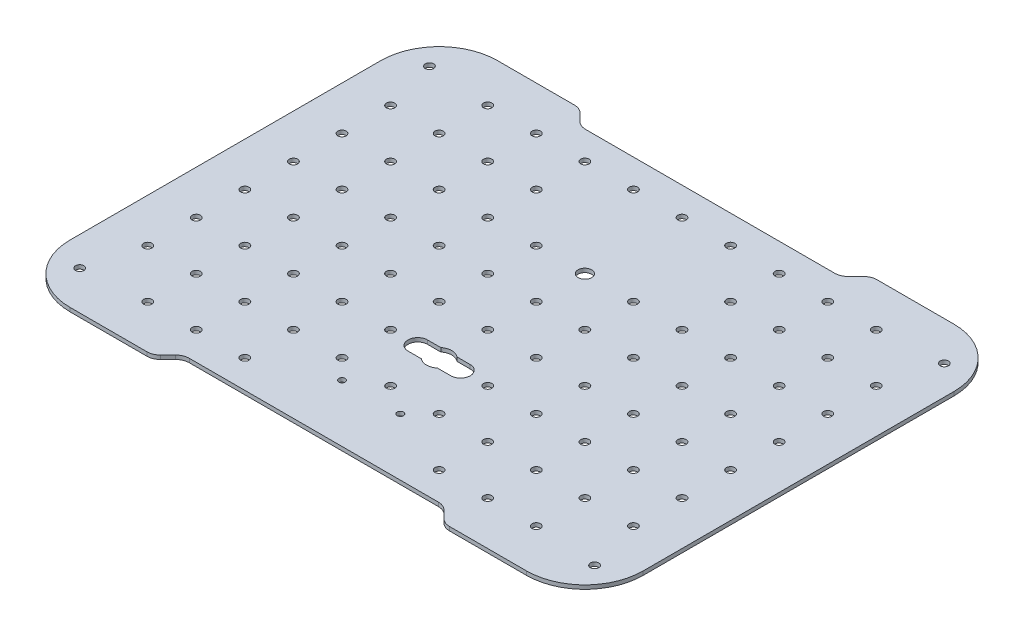
SolidWorks part; units mm, degrees
ref_plane "Front Plane" through (0, 0, 0) normal (0, 0, 1) x (1, 0, 0)
ref_plane "Top Plane" through (0, 0, 0) normal (0, 1, 0) x (1, 0, 0)
ref_plane "Right Plane" through (0, 0, 0) normal (1, 0, 0) x (0, 0, -1)
sketch "Sketch1" plane through (0, 0, 0) normal (0, 1, 0) x (1, 0, 0)
  line L0 (0, 110) -> (0, 0) construction
  line L5 (117.5, -110) -> (-117.5, -110)
  line L6 (147.5, -80) -> (147.5, 80)
  line L7 (117.5, 110) -> (-117.5, 110)
  line L8 (-147.5, -80) -> (-147.5, 80)
  line L9 (0, 0) -> (147.5, 0) construction
  arc A4 (117.5, 110) -> (147.5, 80) centre (117.5, 80) cw
  arc A5 (147.5, -80) -> (117.5, -110) centre (117.5, -80) cw
  arc A6 (-117.5, -110) -> (-147.5, -80) centre (-117.5, -80) cw
  arc A7 (-147.5, 80) -> (-117.5, 110) centre (-117.5, 80) cw
  point P0 (0, 0)
  dimension "D3" = 220
  dimension "D1" = 30
  dimension "D2" = 295
ref_plane "Plane1" through (0, -40, 0) normal (0, 1, 0) x (1, 0, 0)
sketch "Sketch8" plane through (0, 0, 0) normal (0, 1, 0) x (1, 0, 0)
  line L1 (-132.5, -90) -> (132.5, -90) construction
  line L2 (-132.5, -90) -> (-132.5, 90) construction
  line L3 (-132.5, 90) -> (132.5, 90) construction
  line L4 (132.5, -90) -> (132.5, 90) construction
  line L5 (-132.5, -90) -> (132.5, 90) construction
  line L6 (-132.5, 90) -> (132.5, -90) construction
  circle A0 centre (-132.5, 90) radius 2.15
  circle A1 centre (132.5, 90) radius 2.15
  circle A2 centre (-132.5, -90) radius 2.15
  circle A3 centre (132.5, -90) radius 2.15
  point P0 (0, 0)
  dimension "D1" = 4.3
  dimension "D2" = 265
  dimension "D3" = 180
extrude "Boss-Extrude1" add sketch "Sketch1" against normal blind 2
extrude "Cut-Extrude11" cut sketch "Sketch8" against normal through all
sketch "Sketch9" plane through (0, 0, 0) normal (0, 1, 0) x (1, 0, 0)
  line L0 (-75, -110) -> (-67, -102)
  line L1 (-117.5, -110) -> (117.5, -110) construction
  line L2 (-67, -102) -> (67, -102)
  line L3 (67, -102) -> (75, -110)
  line L4 (75, -110) -> (-75, -110)
  line L5 (0, -110) -> (0, -102) construction
  line L6 (0, -102) -> (0, 0) construction
  dimension "D1" = 150
  dimension "D2" = 135
  dimension "D3" = 8
extrude "Cut-Extrude12" cut sketch "Sketch9" against normal through all
mirror "Mirror2" about plane through (0, 0, 0) normal (0, 0, 1) of "Cut-Extrude12"
fillet "Fillet1" radius 7 8 edges at (-67, -1, 102) (67, -1, 102) (75, -1, 110) (-75, -1, 110) (-75, -1, -110) (75, -1, -110) (-67, -1, -102) (67, -1, -102)
sketch "Sketch11" plane through (0, 0, 0) normal (0, 1, 0) x (1, 0, 0)
  line L0 (0, 0) -> (0, -37.5) construction
  circle A0 centre (0, -37.5) radius 6.5
  dimension "D2" = 13
  dimension "D1" = 37.5
extrude "Cut-Extrude14" cut sketch "Sketch11" against normal through all
sketch "Sketch10" plane through (0, 0, 0) normal (0, 1, 0) x (1, 0, 0)
  line L0 (0, 0) -> (0, -37.5) construction
  line L1 (125, -87.5) -> (-125, -87.5) construction
  line L2 (125, -87.5) -> (125, 87.5) construction
  line L3 (125, 87.5) -> (-125, 87.5) construction
  line L4 (-125, -87.5) -> (-125, 87.5) construction
  line L5 (125, -87.5) -> (-125, 87.5) construction
  line L6 (125, 87.5) -> (-125, -87.5) construction
  circle A1 centre (-125, 87.5) radius 2.15
  point P0 (0, 0)
  dimension "D3" = 4.3
  dimension "D1" = 250
  dimension "D4" = 125
  dimension "D5" = 175
extrude "Cut-Extrude13" cut sketch "Sketch10" against normal through all
pattern_linear "LPattern1" count 8 spacing 25 along (0, 0, 1) count 11 spacing 25 along (1, 0, 0) skipping (1, 4), (1, 5), (1, 6), (5, 5), (7, 4), (7, 5), (7, 6) of "Cut-Extrude13"
sketch "Sketch18" plane through (0, 0, 0) normal (0, 1, 0) x (1, 0, 0)
  line L0 (-15, -72.5) -> (15, -72.5) construction
  line L1 (0, -72.5) -> (0, -102) construction
  line L2 (64.1005, -102) -> (-64.1005, -102) construction
  circle A0 centre (15, -72.5) radius 1.65
  circle A1 centre (-15, -72.5) radius 1.65
  dimension "D3" = 3.3
  dimension "D1" = 29.5
  dimension "D2" = 30
extrude "Cut-Extrude21" cut sketch "Sketch18" against normal through all
sketch "Sketch19" plane through (0, 0, 0) normal (0, 1, 0) x (1, 0, 0)
  line L0 (-11, -37.5) -> (11, -37.5) construction
  line L1 (-11, -32.5) -> (11, -32.5)
  line L2 (-11, -42.5) -> (11, -42.5)
  arc A0 (-11, -32.5) -> (-11, -42.5) centre (-11, -37.5) ccw
  arc A1 (11, -42.5) -> (11, -32.5) centre (11, -37.5) ccw
  point P2 (0, -37.5)
  dimension "D1" = 10
  dimension "D2" = 22
extrude "Cut-Extrude22" cut sketch "Sketch19" against normal blind 10
sketch "Sketch20" plane through (0, 0, 0) normal (0, 1, 0) x (1, 0, 0)
  circle A0 centre (125, 87.5) radius 2.15 construction
  circle A1 centre (125, -87.5) radius 2.15 construction
  circle A2 centre (-125, -87.5) radius 2.15 construction
  circle A3 centre (125, 87.5) radius 2.15
  circle A4 centre (125, -87.5) radius 2.15
  circle A5 centre (-125, -87.5) radius 2.15
  circle A6 centre (-125, 87.5) radius 2.15 construction
  circle A7 centre (-125, 87.5) radius 2.15
extrude "Boss-Extrude2" add sketch "Sketch20" against normal up to surface (2 mm away) up to face at (0, -2, 37.5)
sketch "Sketch23" plane through (0, 0, 0) normal (0, 1, 0) x (1, 0, 0)
  circle A0 centre (0, 37.5) radius 3.5
  dimension "D1" = 7
extrude "Cut-Extrude25" cut sketch "Sketch23" against normal blind 10
